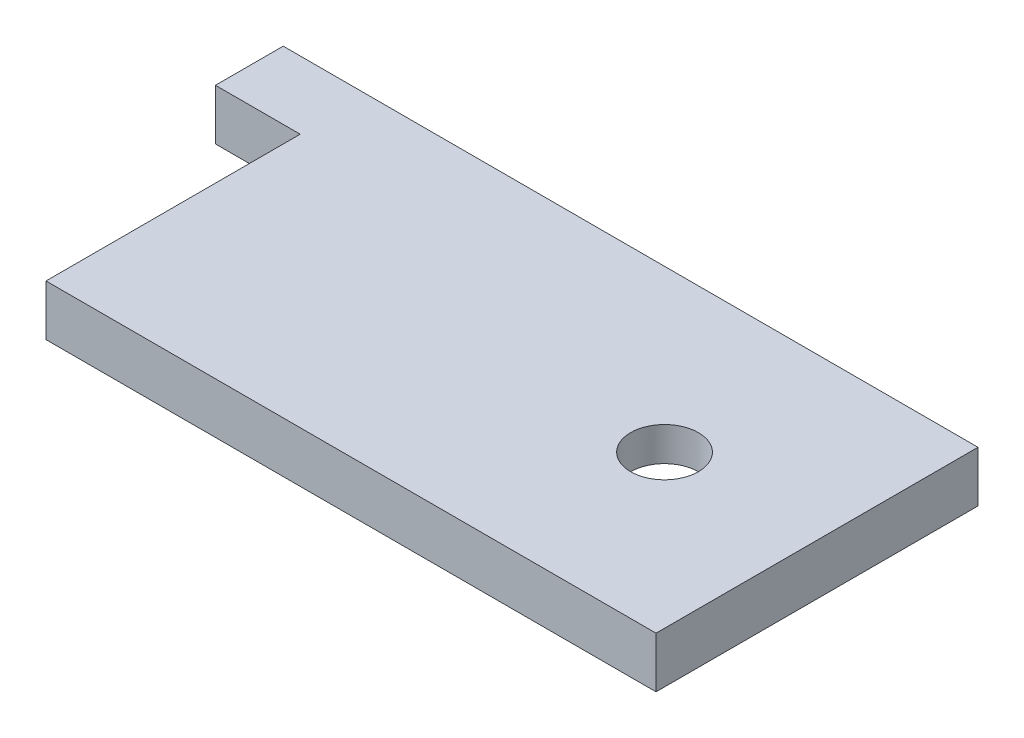
SolidWorks part; units mm, degrees
ref_plane "Přední rovina" through (0, 0, 0) normal (0, 0, 1) x (1, 0, 0)
ref_plane "Horní rovina" through (0, 0, 0) normal (0, 1, 0) x (1, 0, 0)
ref_plane "Pravá rovina" through (0, 0, 0) normal (1, 0, 0) x (0, 0, -1)
sketch "Skica1" plane through (0, 0, 0) normal (0, 0, 1) x (1, 0, 0)
  line L0 (0, 0) -> (0, 7)
  line L1 (0, 7) -> (4, 7)
  line L2 (4, 7) -> (4, 3)
  line L3 (4, 3) -> (36, 3)
  line L4 (36, 3) -> (36, 0)
  line L5 (36, 0) -> (0, 0)
  dimension "D1" = 4
  dimension "D2" = 36
  dimension "D3" = 4
  dimension "D4" = 3
extrude "Přidat vysunutím1" add sketch "Skica1" along normal blind 19
sketch "Skica2" plane through (0, 0, 19) normal (0, 0, 1) x (1, 0, 0)
  line L1 (0, 7) -> (4, 7)
  line L2 (0, 7) -> (0, 3)
  line L3 (0, 3) -> (4, 3)
  line L4 (4, 7) -> (4, 3)
extrude "Odebrat vysunutím1" cut sketch "Skica2" against normal blind 15
sketch "Skica3" plane through (0, 0, 0) normal (0, -1, 0) x (1, 0, 0)
  line L0 (0, 19) -> (0, 0) construction
  line L1 (2, 17) -> (34, 17)
  line L2 (2, 17) -> (2, 2)
  line L3 (2, 2) -> (34, 2)
  line L4 (34, 17) -> (34, 2)
  line L5 (0, 19) -> (36, 19) construction
  dimension "D1" = 2
  dimension "D2" = 2
  dimension "D3" = 15
  dimension "D4" = 32
extrude "Odebrat vysunutím2" cut sketch "Skica3" against normal blind 1
sketch "Skica4" plane through (0, 0, 0) normal (-1, 0, 0) x (0, 0, 1)
  line L1 (0, 7) -> (4, 7)
  line L2 (0, 7) -> (0, 3)
  line L3 (0, 3) -> (4, 3)
  line L4 (4, 7) -> (4, 3)
extrude "Odebrat vysunutím3" cut sketch "Skica4" against normal blind 50
sketch "Skica5" plane through (0, 0, 0) normal (-1, 0, 0) x (0, 0, 1)
  line L0 (19, 0) -> (0, 0) construction
  line L1 (0, 3) -> (4, 3)
  line L2 (0, 3) -> (0, 0)
  line L3 (0, 0) -> (4, 0)
  line L4 (4, 3) -> (4, 0)
  dimension "D1" = 4
extrude "Přidat vysunutím2" add sketch "Skica5" along normal blind 5
sketch "Skica6" plane through (0, 1, 0) normal (0, -1, 0) x (1, 0, 0)
  line L0 (34, 2) -> (34, 17) construction
  line L2 (34, 17) -> (2, 17) construction
  circle A0 centre (27, 9.5) radius 2
  dimension "D1" = 4
  dimension "D2" = 7
  dimension "D3" = 7.5
extrude "Odebrat vysunutím4" cut sketch "Skica6" against normal blind 5
